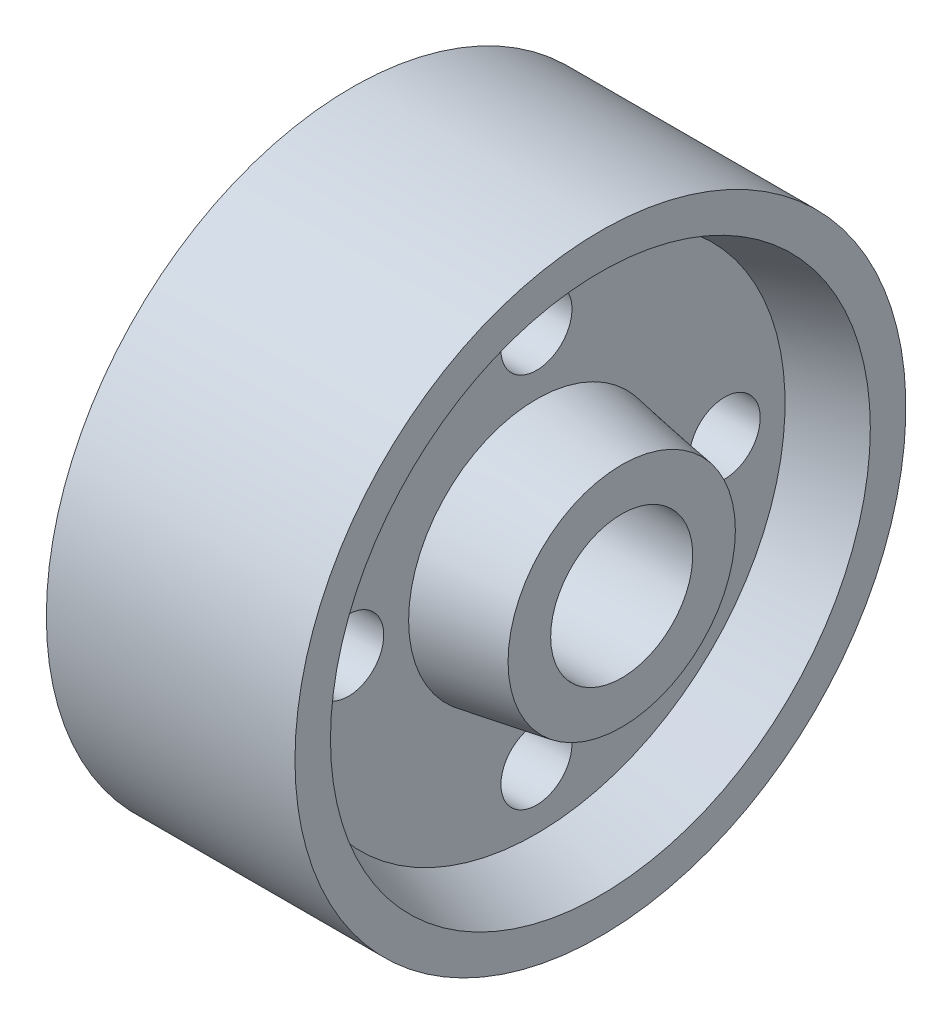
SolidWorks part; units mm, degrees
ref_plane "Front Plane" through (0, 0, 0) normal (0, 0, 1) x (1, 0, 0)
ref_plane "Top Plane" through (0, 0, 0) normal (0, 1, 0) x (1, 0, 0)
ref_plane "Right Plane" through (0, 0, 0) normal (1, 0, 0) x (0, 0, -1)
sketch "Sketch1" plane through (0, 0, 0) normal (0, 1, 0) x (1, 0, 0)
  line L0 (0, 0) -> (86.9592, 0) construction
  line L1 (0, 0) -> (0, 16)
  line L2 (0, 16) -> (12, 18)
  line L3 (12, 18) -> (12, 35)
  line L4 (12, 35) -> (3, 38)
  line L5 (3, 38) -> (3, 43)
  line L6 (3, 43) -> (38, 43)
  line L7 (20.5, 43) -> (20.5, 0) construction
  line L8 (41, 0) -> (41, 16)
  line L9 (41, 16) -> (29, 18)
  line L10 (29, 18) -> (29, 35)
  line L11 (29, 35) -> (38, 38)
  line L12 (38, 38) -> (38, 43)
  line L13 (0, 0) -> (41, 0)
  dimension "D1" = 32
  dimension "D2" = 36
  dimension "D3" = 70
  dimension "D4" = 76
  dimension "D5" = 86
  dimension "D6" = 20.5
  dimension "D7" = 17.5
  dimension "D8" = 12
revolve "Revolve1" add sketch "Sketch1" angle 360 about L0
sketch "Sketch2" plane through (0, 0, 0) normal (-1, 0, 0) x (0, 0, 1)
  circle A0 centre (0, 0) radius 26.5 construction
  circle A1 centre (0, 26.5) radius 5
  circle A2 centre (26.5, 0) radius 5
  circle A3 centre (0, -26.5) radius 5
  circle A4 centre (-26.5, 0) radius 5
  point P5 (0, 0)
  point P14 (0, 0)
  dimension "D1" = 53
  dimension "D2" = 10
  dimension "D3" = 4
extrude "Cut-Extrude1" cut sketch "Sketch2" against normal through all
sketch "Sketch3" plane through (0, 0, 0) normal (-1, 0, 0) x (0, 0, 1)
  circle A0 centre (0, 0) radius 10
  dimension "D1" = 20
extrude "Cut-Extrude2" cut sketch "Sketch3" against normal through all
